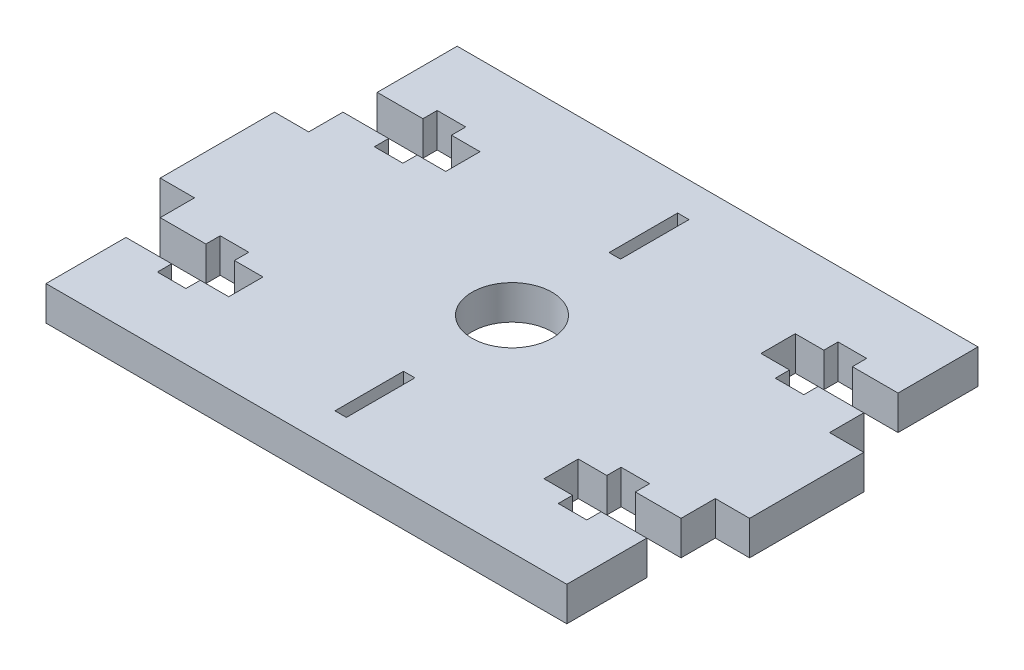
SolidWorks part; units mm, degrees
material "Cedro"
ref_plane "Plano frontal" through (0, 0, 0) normal (0, 0, 1) x (1, 0, 0)
ref_plane "Plano superior" through (0, 0, 0) normal (0, 1, 0) x (1, 0, 0)
ref_plane "Plano direito" through (0, 0, 0) normal (1, 0, 0) x (0, 0, -1)
sketch "Esboço4" plane through (0, 0, 0) normal (0, 1, 0) x (1, 0, 0)
  line L0 (19.1, 6.75) -> (16.6, 6.75)
  line L1 (16.6, 6.75) -> (16.6, 8)
  line L2 (14.1, 8) -> (14.1, 11)
  line L3 (16.6, 8) -> (14.1, 8)
  line L4 (14.1, 11) -> (16.6, 11)
  line L5 (16.6, 11) -> (16.6, 12.25)
  line L6 (16.6, 12.25) -> (19.1, 12.25)
  line L7 (0.3, -15) -> (-0.2, -15)
  line L8 (-0.2, -15) -> (-0.2, -9)
  line L9 (-0.2, -9) -> (0.8, -9)
  line L10 (0.8, -9) -> (0.8, -15)
  line L11 (0.8, -15) -> (0.3, -15)
  line L12 (0.8, 15) -> (0.3, 15)
  line L13 (0.8, 9) -> (0.8, 15)
  line L14 (-0.2, 9) -> (0.8, 9)
  line L15 (-0.2, 15) -> (-0.2, 9)
  line L16 (0.3, 15) -> (-0.2, 15)
  line L17 (19.1, 12.25) -> (19.1, 11)
  line L18 (19.1, 11) -> (23.1, 11)
  line L19 (19.1, 6.75) -> (19.1, 8)
  line L20 (19.1, 8) -> (23.1, 8)
  line L21 (19.1, -12.25) -> (16.6, -12.25)
  line L22 (16.6, -12.25) -> (16.6, -11)
  line L23 (14.1, -11) -> (14.1, -8)
  line L24 (16.6, -11) -> (14.1, -11)
  line L25 (14.1, -8) -> (16.6, -8)
  line L26 (16.6, -8) -> (16.6, -6.75)
  line L27 (16.6, -6.75) -> (19.1, -6.75)
  line L28 (19.1, -6.75) -> (19.1, -8)
  line L29 (19.1, -8) -> (23.1, -8)
  line L30 (19.1, -12.25) -> (19.1, -11)
  line L31 (19.1, -11) -> (23.1, -11)
  line L33 (-18.5, -11) -> (-22.5, -11)
  line L34 (-18.5, -12.25) -> (-18.5, -11)
  line L35 (-18.5, -8) -> (-22.5, -8)
  line L36 (-18.5, -6.75) -> (-18.5, -8)
  line L37 (-16, -6.75) -> (-18.5, -6.75)
  line L38 (-16, -8) -> (-16, -6.75)
  line L39 (-13.5, -8) -> (-16, -8)
  line L40 (-16, -11) -> (-13.5, -11)
  line L41 (-13.5, -11) -> (-13.5, -8)
  line L42 (-16, -12.25) -> (-16, -11)
  line L43 (-18.5, -12.25) -> (-16, -12.25)
  line L44 (-18.5, 8) -> (-22.5, 8)
  line L45 (-18.5, 6.75) -> (-18.5, 8)
  line L46 (-18.5, 11) -> (-22.5, 11)
  line L47 (-18.5, 12.25) -> (-18.5, 11)
  line L48 (-16, 12.25) -> (-18.5, 12.25)
  line L49 (-16, 11) -> (-16, 12.25)
  line L50 (-13.5, 11) -> (-16, 11)
  line L51 (-16, 8) -> (-13.5, 8)
  line L52 (-13.5, 8) -> (-13.5, 11)
  line L53 (-16, 6.75) -> (-16, 8)
  line L54 (-18.5, 6.75) -> (-16, 6.75)
  line L55 (26.1, 5) -> (23.1, 5)
  line L56 (-22.5, -5) -> (-22.5, -8)
  line L57 (-22.5, 5) -> (-22.5, 8)
  line L58 (23.1, -5) -> (23.1, -8)
  line L59 (23.1, 5) -> (23.1, 8)
  line L60 (-22.5, -5) -> (-25.5, -5)
  line L61 (-0.5, 18) -> (23.1, 18)
  line L62 (23.1, -18) -> (23.1, -11)
  line L63 (-22.5, -11) -> (-22.5, -18)
  line L64 (-22.5, -18) -> (-0.5, -18)
  line L65 (-0.5, -18) -> (23.1, -18)
  line L66 (-22.5, 11) -> (-22.5, 18)
  line L67 (-22.5, 18) -> (-0.5, 18)
  line L68 (23.1, 11) -> (23.1, 18)
  line L70 (-25.5, -5) -> (-25.5, 5)
  line L71 (-25.5, 5) -> (-22.5, 5)
  line L72 (26.1, -5) -> (26.1, 5)
  line L73 (23.1, -5) -> (26.1, -5)
  circle A0 centre (0.3, 0) radius 3.5
extrude "Ressalto-extrusão1" add sketch "Esboço4" along normal blind 3
